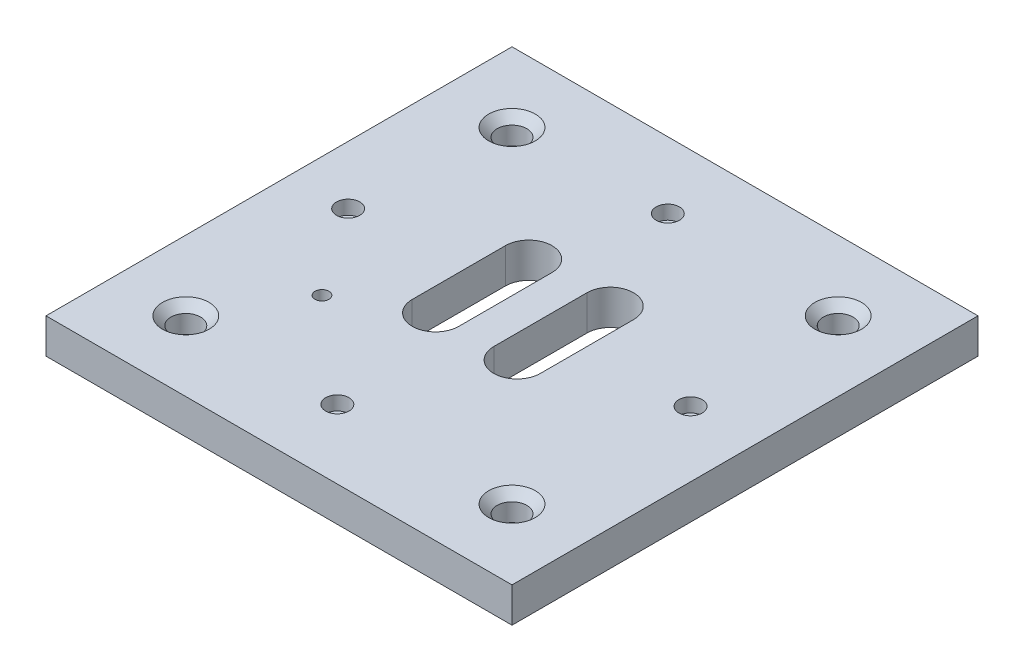
SolidWorks part; units mm, degrees
ref_plane "Ön Düzlem" through (0, 0, 0) normal (0, 0, 1) x (1, 0, 0)
ref_plane "Üst Düzlem" through (0, 0, 0) normal (0, 1, 0) x (1, 0, 0)
ref_plane "Sağ Düzlem" through (0, 0, 0) normal (1, 0, 0) x (0, 0, -1)
sketch "Çizim1" plane through (0, 0, 0) normal (0, 1, 0) x (1, 0, 0)
  line L1 (-200, -200) -> (200, -200)
  line L2 (-200, -200) -> (-200, 200)
  line L3 (-200, 200) -> (200, 200)
  line L4 (200, -200) -> (200, 200)
  line L5 (-200, -200) -> (200, 200) construction
  line L6 (-200, 200) -> (200, -200) construction
  point P0 (0, 0)
  dimension "D1" = 400
  dimension "D2" = 400
extrude "Yükseklik-Ekstrüzyon1" add sketch "Çizim1" along normal blind 30
hole_wizard "Ø25.5 (25.5) Çap Delik1" positions "Çizim2" profile "Çizim3" hole size "Ø25.5" standard "ANSI Metrik" end condition through all
sketch "Çizim2" plane through (0, 30, 0) normal (0, 1, 0) x (1, 0, 0)
  point P0 (-140, -140)
  point P2 (-140, 140)
  point P4 (140, -140)
  point P6 (140, 140)
  dimension "D1" = 280
  dimension "D2" = 140
  dimension "D3" = 280
  dimension "D4" = 140
sketch "Çizim3" plane through (-140, 30, 140) normal (1, 0, 0) x (0, 0, 1)
  line L0 (0, 0) -> (0, 30)
  line L1 (0, 30) -> (20, 30)
  line L2 (12.75, 22.75) -> (12.75, 7.25)
  line L3 (12.75, 7.25) -> (20, 0)
  line L5 (20, 0) -> (0, 0)
  line L6 (-12.75, 7.25) -> (-20, 0) construction
  line L7 (20, 30) -> (12.75, 22.75)
  line L8 (-20, 30) -> (-12.75, 22.75) construction
  line L11 (0, -6.35) -> (0, 107.95) construction
  dimension "Thru Hole Dia." = 25.5
  dimension "Thru Hole Depth" = 30
  dimension "Near C'Sink Dia." = 40
  dimension "Near C'Sink Angle" = 90
  dimension "Far C'Sink Dia." = 40
  dimension "Far C'Sink Angle" = 90
sketch "Çizim4" plane through (0, 30, 0) normal (0, 1, 0) x (1, 0, 0)
  line L0 (-35, 49.3521) -> (-35, -30.6479)
  line L1 (-15, 49.3521) -> (-15, -30.6479)
  line L2 (-55, 49.3521) -> (-55, -30.6479)
  line L3 (35, 49.3521) -> (35, -30.6479)
  line L4 (55, 49.3521) -> (55, -30.6479)
  line L5 (15, 49.3521) -> (15, -30.6479)
  arc A0 (-15, 49.3521) -> (-55, 49.3521) centre (-35, 49.3521) ccw
  arc A1 (-55, -30.6479) -> (-15, -30.6479) centre (-35, -30.6479) ccw
  arc A2 (55, 49.3521) -> (15, 49.3521) centre (35, 49.3521) ccw
  arc A3 (15, -30.6479) -> (55, -30.6479) centre (35, -30.6479) ccw
  point P2 (-35, 9.3521)
  point P7 (35, 9.3521)
  dimension "D3" = 20
  dimension "D1" = 35
  dimension "D2" = 35
  dimension "D4" = 40
extrude "Kes-Ekstrüzyon3" cut sketch "Çizim4" against normal blind 30
hole_wizard "M12 SHCS İçin Havşa1" positions "Çizim7" profile "Çizim8" size "M12" standard "ANSI Metrik" slot yes end condition through all
sketch "Çizim7" plane through (0, 30, 0) normal (0, 1, 0) x (1, 0, 0)
  point P0 (-9.136, -140.7788)
  point P2 (-149.9933, 9.3521)
  point P4 (-9.136, 142.8614)
  point P6 (143.8963, 9.3521)
sketch "Çizim8" plane through (-9.136, 30, 140.7788) normal (1, 0, 0) x (0, 0, 1)
  line L0 (0, 0) -> (0, 30)
  line L1 (0, 30) -> (6.5, 30)
  line L3 (6.5, 30) -> (6.5, 12)
  line L4 (6.5, 12) -> (10, 12)
  line L5 (10, 12) -> (10, 0)
  line L7 (10, 0) -> (0, 0)
  line L11 (0, -6.35) -> (0, 107.95) construction
  dimension "Thru Hole Dia." = 13
  dimension "Thru Hole Depth" = 30
  dimension "C'Bore Dia." = 20
  dimension "C'Bore Depth" = 12
hole_wizard "M14x2.0 Dişli Delik1" positions "Çizim9" profile "Çizim10" tap size "M14x2.0" standard "ANSI Metrik"
sketch "Çizim9" plane through (0, 30, 0) normal (0, 1, 0) x (1, 0, 0)
  point P0 (-96.8219, -66.29)
sketch "Çizim10" plane through (-96.8219, 30, 66.29) normal (1, 0, 0) x (0, 0, 1)
  line L0 (0, 0) -> (0, 23.6052)
  line L1 (0, 23.6052) -> (6, 20)
  line L2 (6, 20) -> (6, 0)
  line L5 (6, 0) -> (0, 0)
  line L10 (0, 23.6052) -> (-6, 20) construction
  line L11 (0, -6.35) -> (0, 107.95) construction
  dimension "Tap Drill Dia." = 12
  dimension "Tap Drill Depth" = 20
  dimension "Drill Angle" = 118
cosmetic thread "Delik Dişi1" parameters "D1"=20, "D2"=14
